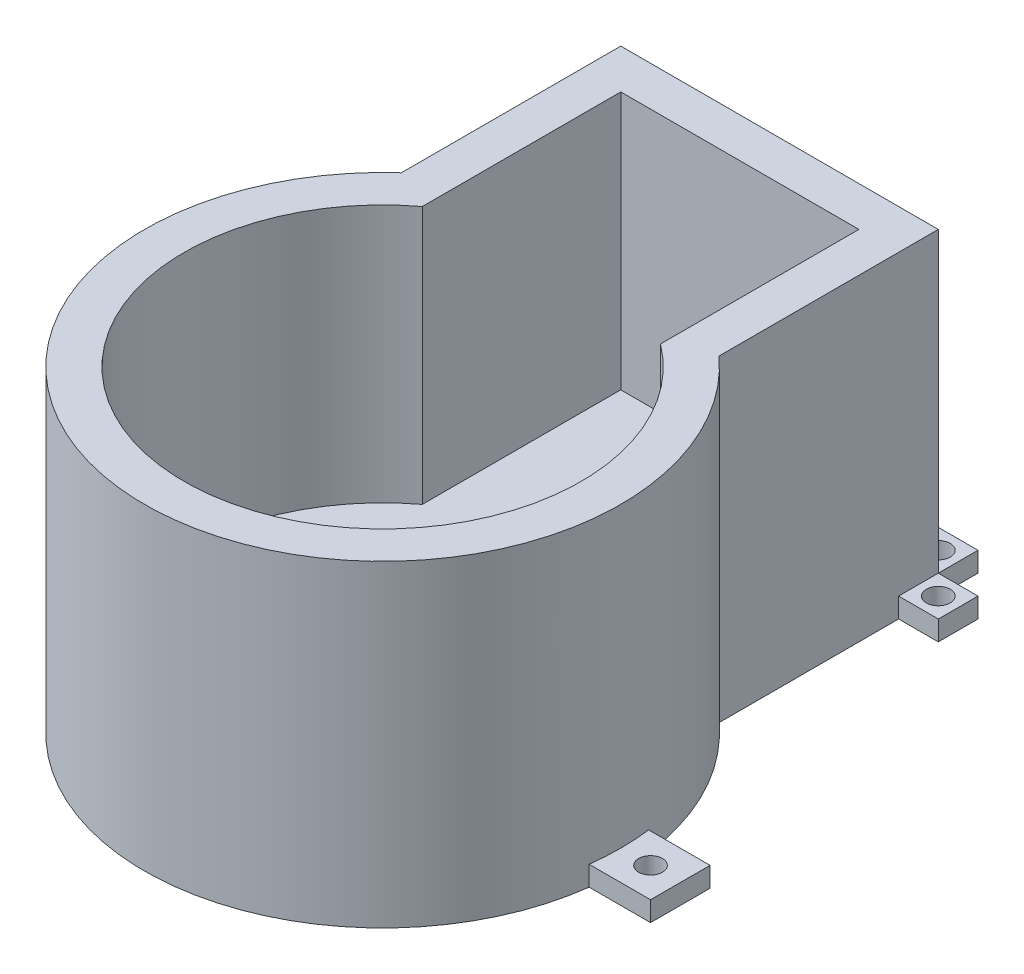
SolidWorks part; units mm, degrees
ref_plane "Front Plane" through (0, 0, 0) normal (0, 0, 1) x (1, 0, 0)
ref_plane "Top Plane" through (0, 0, 0) normal (0, 1, 0) x (1, 0, 0)
ref_plane "Right Plane" through (0, 0, 0) normal (1, 0, 0) x (0, 0, -1)
sketch "Sketch1" plane through (0, 0, 0) normal (0, 1, 0) x (1, 0, 0)
  line L0 (0, 40) -> (0, -40) construction
  line L1 (-40, 40) -> (40, 40)
  line L2 (-40, 40) -> (-40, -40)
  line L3 (-40, -40) -> (40, -40)
  line L4 (40, 40) -> (40, -40)
  line L5 (-40, 40) -> (40, -40) construction
  line L6 (-40, -40) -> (40, 40) construction
  circle A0 centre (0, -60) radius 60
  point P0 (0, 0)
  dimension "D4" = 120
  dimension "D1" = 80
  dimension "D2" = 80
  dimension "D3" = 60
extrude "Boss-Extrude1" add sketch "Sketch1" along normal blind 80
sketch "Sketch2" plane through (0, 80, 0) normal (0, 1, 0) x (1, 0, 0)
  line L1 (-30, 30) -> (30, 30)
  line L2 (-30, 30) -> (-30, -30)
  line L3 (-30, -30) -> (30, -30)
  line L4 (30, 30) -> (30, -30)
  line L5 (-30, 30) -> (30, -30) construction
  line L6 (-30, -30) -> (30, 30) construction
  circle A0 centre (0, -60) radius 50
  point P0 (0, 0)
  dimension "D3" = 100
  dimension "D1" = 60
  dimension "D2" = 60
extrude "Cut-Extrude1" cut sketch "Sketch2" against normal blind 65 contours A0 L4 L1 L2 | L4 A0 L2 L3 | L2 A0 L4 L3
sketch "Sketch3" plane through (0, 0, 0) normal (0, -1, 0) x (1, 0, 0)
  line L0 (0, 120) -> (0, -40) construction
  line L1 (30, -30) -> (50, -30)
  line L2 (30, -30) -> (30, -50)
  line L3 (30, -50) -> (50, -50)
  line L4 (50, -30) -> (50, -50)
  line L5 (30, -30) -> (50, -50) construction
  line L6 (30, -50) -> (50, -30) construction
  line L7 (-40, -40) -> (40, -40) construction
  line L8 (-30, -50) -> (-50, -30) construction
  line L9 (50, -50) -> (40, -50)
  line L10 (50, -50) -> (50, -40)
  line L11 (50, -40) -> (40, -40)
  line L12 (40, -50) -> (40, -40)
  line L13 (-30, -30) -> (-50, -50) construction
  line L14 (-40, -50) -> (-40, -40)
  line L15 (-50, -40) -> (-40, -40)
  line L16 (-50, -50) -> (-50, -40)
  line L17 (-50, -50) -> (-40, -50)
  line L18 (-50, -30) -> (-50, -50)
  line L19 (-30, -50) -> (-50, -50)
  line L20 (-30, -30) -> (-30, -50)
  line L21 (-30, -30) -> (-50, -30)
  line L22 (-60, 60) -> (60, 60) construction
  line L23 (-60, 60) -> (-75, 60) construction
  line L24 (-75, 67.5) -> (75, 67.5)
  line L25 (-75, 67.5) -> (-75, 52.5)
  line L26 (-75, 52.5) -> (75, 52.5)
  line L27 (75, 67.5) -> (75, 52.5)
  line L28 (-75, 67.5) -> (75, 52.5) construction
  line L29 (-75, 52.5) -> (75, 67.5) construction
  arc A0 (40, 15.2786) -> (-40, 15.2786) centre (0, 60) ccw construction
  circle A1 centre (45, -35) radius 3
  circle A2 centre (35, -45) radius 3
  circle A3 centre (-35, -45) radius 3
  circle A4 centre (-45, -35) radius 3
  circle A6 centre (-67.5, 60) radius 3
  circle A7 centre (67.5, 60) radius 3
  point P0 (40, -40)
  point P31 (-40, -40)
  point P35 (0, 60)
  arc M17 (40, 15.2786) -> (-40, 15.2786) centre (0, 60) ccw
  line M18 (-40, 15.2786) -> (-40, -40)
  line M19 (-40, -40) -> (40, -40)
  line M20 (40, -40) -> (40, 15.2786)
  dimension "D3" = 6
  dimension "D4" = 6
  dimension "D11" = 6
  dimension "D1" = 20
  dimension "D2" = 20
  dimension "D5" = 5
  dimension "D6" = 5
  dimension "D7" = 5
  dimension "D8" = 5
  dimension "D9" = 15
  dimension "D10" = 150
extrude "Boss-Extrude2" add sketch "Sketch3" against normal blind 5 contours L25 L26 L24 A6 M17 | L27 L24 L26 A7 M17 | L21 L18 L15 A4 M18 | L20 L14 L19 A3 M19 | L3 L12 L2 A2 M19 | L11 L4 L1 A1 M20
